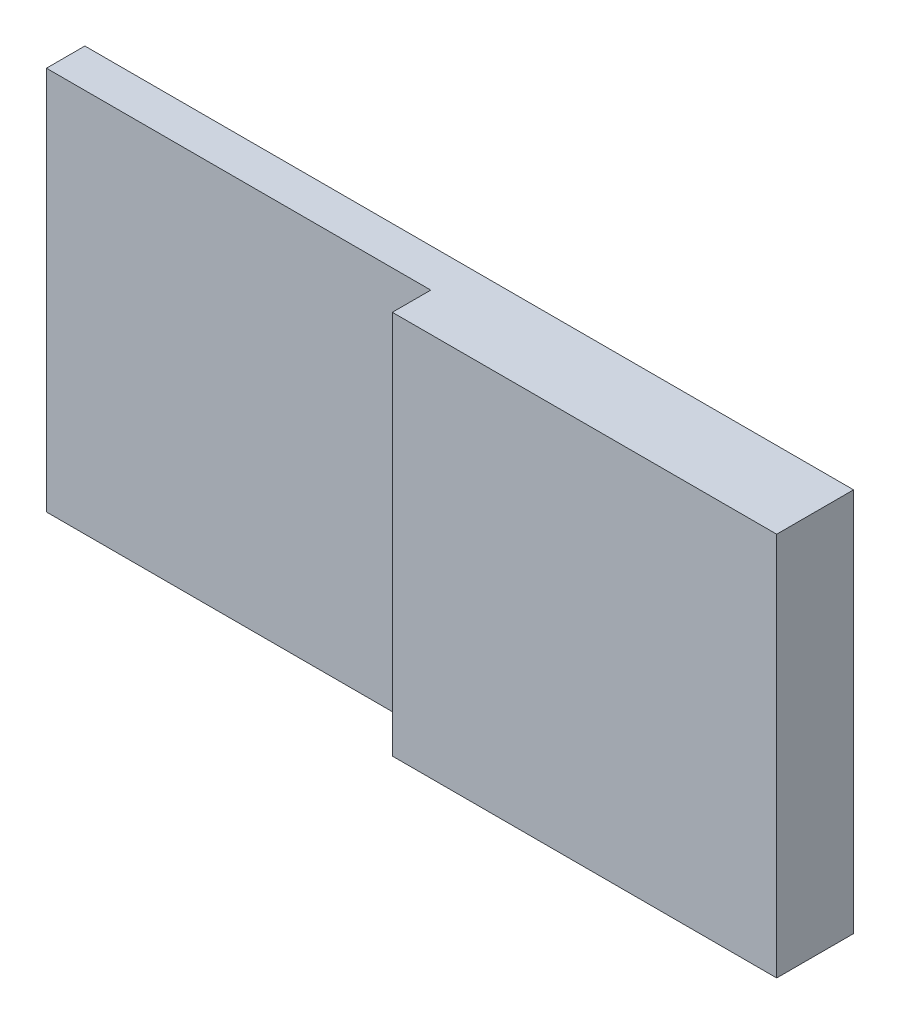
SolidWorks part; units mm, degrees
ref_plane "前视基准面" through (0, 0, 0) normal (0, 0, 1) x (1, 0, 0)
ref_plane "上视基准面" through (0, 0, 0) normal (0, 1, 0) x (1, 0, 0)
ref_plane "右视基准面" through (0, 0, 0) normal (1, 0, 0) x (0, 0, -1)
sketch "草图1" plane through (0, 0, 0) normal (0, 0, 1) x (1, 0, 0)
  line L1 (-100, -50) -> (100, -50)
  line L2 (-100, -50) -> (-100, 50)
  line L3 (-100, 50) -> (100, 50)
  line L4 (100, -50) -> (100, 50)
  line L5 (-100, -50) -> (100, 50) construction
  line L6 (-100, 50) -> (100, -50) construction
  point P0 (0, 0)
  dimension "D1" = 200
  dimension "D2" = 100
extrude "凸台-拉伸1" add sketch "草图1" along normal blind 10
sketch "草图2" plane through (0, 0, 10) normal (0, 0, 1) x (1, 0, 0)
  line L0 (100, 50) -> (-100, 50) construction
  line L1 (0, 50) -> (100, 50)
  line L2 (0, 50) -> (0, -50)
  line L3 (0, -50) -> (100, -50)
  line L4 (100, 50) -> (100, -50)
extrude "凸台-拉伸2" add sketch "草图2" along normal blind 10
